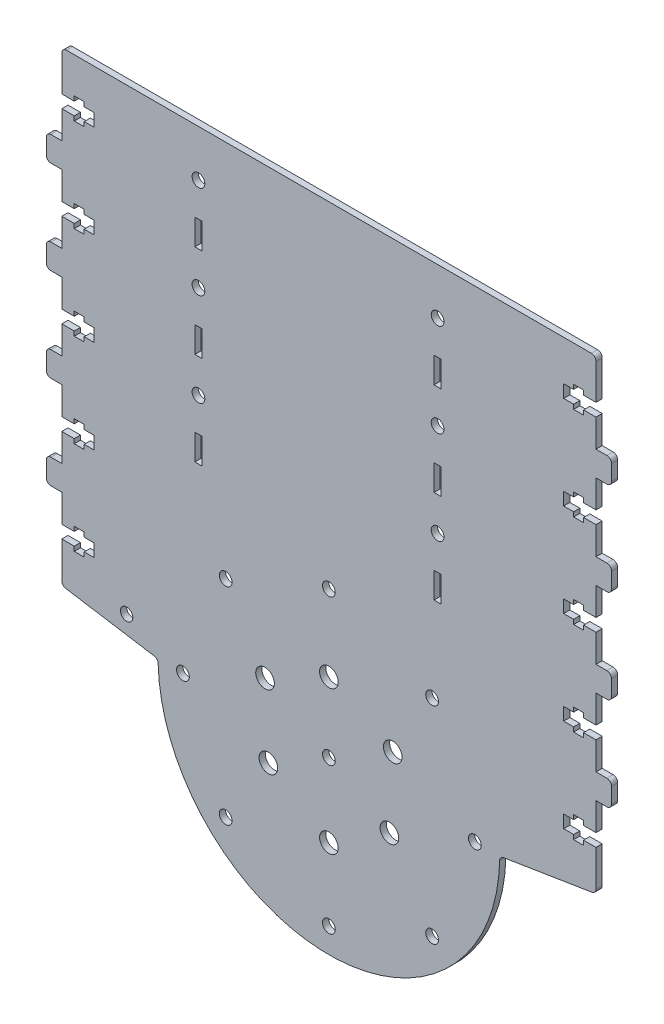
SolidWorks part; units mm, degrees
ref_plane "前视基准面" through (0, 0, 0) normal (0, 0, 1) x (1, 0, 0)
ref_plane "上视基准面" through (0, 0, 0) normal (0, 1, 0) x (1, 0, 0)
ref_plane "右视基准面" through (0, 0, 0) normal (1, 0, 0) x (0, 0, -1)
sketch "草图1" plane through (0, 0, 0) normal (0, 0, 1) x (1, 0, 0)
  line L9 (143, 45.95) -> (147, 45.95)
  line L10 (147, 45.95) -> (147, 44.5)
  line L11 (147, 44.5) -> (150.2, 44.5)
  line L12 (150.2, 44.5) -> (150.2, 45.95)
  line L13 (150.2, 45.95) -> (153.4, 45.95)
  line L14 (153.4, 45.95) -> (153.4, 50.05)
  line L23 (143, 48) -> (141.6922, 48) construction
  line L24 (143, 45.95) -> (143, 50.05) construction
  line L25 (150.2, 51.5) -> (150.2, 50.05)
  line L26 (147, 50.05) -> (147, 51.5)
  line L27 (150.2, 50.05) -> (153.4, 50.05)
  line L28 (147, 51.5) -> (150.2, 51.5)
  line L29 (143, 50.05) -> (147, 50.05)
  line L31 (143, 29) -> (138, 29)
  line L32 (138, 29) -> (138, 37)
  line L33 (138, 37) -> (143, 37)
  line L34 (143, 37) -> (143, 45.95)
  line L35 (138, 33) -> (143, 33) construction
  line L43 (143, 119) -> (143, 123)
  line L44 (229, -79) -> (229, -87) construction
  line L45 (143, 20.05) -> (143, 15.95) construction
  line L69 (143, -97) -> (311, -97) construction
  line L70 (143, 18) -> (141.6922, 18) construction
  line L71 (143, 15.95) -> (147, 15.95)
  line L72 (147, 15.95) -> (147, 14.5)
  line L73 (147, 14.5) -> (150.2, 14.5)
  line L98 (150.2, 14.5) -> (150.2, 15.95)
  line L123 (150.2, 15.95) -> (153.4, 15.95)
  line L124 (150.2, 21.5) -> (150.2, 20.05)
  line L125 (147, 20.05) -> (147, 21.5)
  line L126 (150.2, 20.05) -> (153.4, 20.05)
  line L127 (147, 21.5) -> (150.2, 21.5)
  line L128 (143, 20.05) -> (147, 20.05)
  line L129 (143, 7) -> (143, 15.95)
  line L130 (143, 15.95) -> (147, 15.95)
  line L131 (147, 14.5) -> (150.2, 14.5)
  line L132 (143, 15.95) -> (147, 15.95)
  line L133 (147, 15.95) -> (147, 14.5)
  line L134 (147, 14.5) -> (150.2, 14.5)
  line L135 (150.2, 14.5) -> (150.2, 15.95)
  line L136 (150.2, 15.95) -> (153.4, 15.95)
  line L137 (150.2, 21.5) -> (150.2, 20.05)
  line L138 (147, 20.05) -> (147, 21.5)
  line L139 (150.2, 20.05) -> (153.4, 20.05)
  line L140 (147, 21.5) -> (150.2, 21.5)
  line L141 (143, 20.05) -> (147, 20.05)
  line L142 (150.2, 15.95) -> (153.4, 15.95)
  line L143 (147, 15.95) -> (147, 14.5)
  line L144 (150.2, 14.5) -> (150.2, 15.95)
  line L145 (150.2, 20.05) -> (153.4, 20.05)
  line L146 (150.2, 21.5) -> (150.2, 20.05)
  line L147 (147, 21.5) -> (150.2, 21.5)
  line L148 (147, 20.05) -> (147, 21.5)
  line L149 (143, 20.05) -> (147, 20.05)
  line L150 (143, 45.95) -> (147, 45.95)
  line L151 (147, 45.95) -> (147, 44.5)
  line L152 (147, 44.5) -> (150.2, 44.5)
  line L153 (150.2, 44.5) -> (150.2, 45.95)
  line L154 (150.2, 45.95) -> (153.4, 45.95)
  line L155 (150.2, 51.5) -> (150.2, 50.05)
  line L156 (147, 50.05) -> (147, 51.5)
  line L157 (150.2, 50.05) -> (153.4, 50.05)
  line L158 (143, 45.95) -> (147, 45.95)
  line L159 (147, 44.5) -> (150.2, 44.5)
  line L160 (150.2, 45.95) -> (153.4, 45.95)
  line L161 (147, 45.95) -> (147, 44.5)
  line L162 (150.2, 44.5) -> (150.2, 45.95)
  line L163 (150.2, 50.05) -> (153.4, 50.05)
  line L164 (150.2, 51.5) -> (150.2, 50.05)
  line L165 (147, 51.5) -> (150.2, 51.5)
  line L166 (147, 50.05) -> (147, 51.5)
  line L167 (143, 50.05) -> (147, 50.05)
  line L168 (147, 51.5) -> (150.2, 51.5)
  line L169 (143, 50.05) -> (147, 50.05)
  line L170 (143, 29) -> (143, 20.05)
  line L171 (143, 15.95) -> (147, 15.95)
  line L172 (147, 14.5) -> (150.2, 14.5)
  line L173 (150.2, 15.95) -> (153.4, 15.95)
  line L174 (147, 15.95) -> (147, 14.5)
  line L175 (150.2, 14.5) -> (150.2, 15.95)
  line L177 (153.4, 20.05) -> (153.4, 15.95)
  line L178 (150.2, 20.05) -> (153.4, 20.05)
  line L179 (150.2, 21.5) -> (150.2, 20.05)
  line L180 (147, 21.5) -> (150.2, 21.5)
  line L181 (147, 20.05) -> (147, 21.5)
  line L182 (143, 20.05) -> (147, 20.05)
  line L183 (138, 3) -> (143, 3) construction
  line L184 (138, -1) -> (143, -1)
  line L185 (138, 7) -> (138, -1)
  line L186 (143, 7) -> (138, 7)
  line L187 (138, 93) -> (143, 93) construction
  line L188 (143, 78) -> (141.6922, 78) construction
  line L189 (272.15, 28.85) -> (269.85, 37.15) construction
  line L190 (138, 63) -> (143, 63) construction
  line L191 (143, 89) -> (138, 89)
  line L192 (138, 89) -> (138, 97)
  line L193 (138, 97) -> (143, 97)
  line L194 (143, 75.95) -> (147, 75.95)
  line L195 (147, 75.95) -> (147, 74.5)
  line L196 (147, 74.5) -> (150.2, 74.5)
  line L197 (150.2, 74.5) -> (150.2, 75.95)
  line L198 (150.2, 75.95) -> (153.4, 75.95)
  line L199 (143, 59) -> (143, 50.05)
  line L200 (138, 59) -> (143, 59)
  line L201 (153.4, 75.95) -> (153.4, 80.05)
  line L202 (150.2, 81.5) -> (150.2, 80.05)
  line L203 (143, 45.95) -> (147, 45.95)
  line L204 (147, 44.5) -> (150.2, 44.5)
  line L205 (150.2, 45.95) -> (153.4, 45.95)
  line L206 (147, 45.95) -> (147, 44.5)
  line L207 (150.2, 44.5) -> (150.2, 45.95)
  line L208 (150.2, 50.05) -> (153.4, 50.05)
  line L209 (150.2, 51.5) -> (150.2, 50.05)
  line L210 (147, 51.5) -> (150.2, 51.5)
  line L211 (147, 50.05) -> (147, 51.5)
  line L212 (143, 50.05) -> (147, 50.05)
  line L213 (272.15, 37.15) -> (269.85, 28.85) construction
  line L214 (147, 80.05) -> (147, 81.5)
  line L215 (150.2, 80.05) -> (153.4, 80.05)
  line L216 (147, 81.5) -> (150.2, 81.5)
  line L217 (143, 80.05) -> (147, 80.05)
  line L218 (143, 67) -> (143, 75.95)
  line L219 (143, 75.95) -> (147, 75.95)
  line L220 (147, 75.95) -> (147, 74.5)
  line L221 (147, 74.5) -> (150.2, 74.5)
  line L222 (150.2, 74.5) -> (150.2, 75.95)
  line L223 (150.2, 75.95) -> (153.4, 75.95)
  line L224 (150.2, 81.5) -> (150.2, 80.05)
  line L225 (147, 80.05) -> (147, 81.5)
  line L227 (271, 48) -> (271, 33) construction
  line L228 (272.15, 58.85) -> (269.85, 67.15) construction
  line L229 (272.15, 67.15) -> (269.85, 58.85) construction
  line L230 (150.2, 80.05) -> (153.4, 80.05)
  line L231 (143, 75.95) -> (147, 75.95)
  line L232 (147, 74.5) -> (150.2, 74.5)
  line L233 (150.2, 75.95) -> (153.4, 75.95)
  line L234 (147, 75.95) -> (147, 74.5)
  line L235 (150.2, 74.5) -> (150.2, 75.95)
  line L253 (150.2, 80.05) -> (153.4, 80.05)
  line L254 (150.2, 81.5) -> (150.2, 80.05)
  line L255 (143, -27) -> (143, -97) construction
  line L256 (147, 81.5) -> (150.2, 81.5)
  line L257 (147, 80.05) -> (147, 81.5)
  line L258 (143, 80.05) -> (147, 80.05)
  line L259 (147, 81.5) -> (150.2, 81.5)
  line L260 (143, 80.05) -> (147, 80.05)
  line L261 (143, 89) -> (143, 80.05)
  line L262 (143, 75.95) -> (147, 75.95)
  line L263 (147, 74.5) -> (150.2, 74.5)
  line L264 (150.2, 75.95) -> (153.4, 75.95)
  line L265 (147, 75.95) -> (147, 74.5)
  line L267 (150.2, 74.5) -> (150.2, 75.95)
  line L269 (150.2, 80.05) -> (153.4, 80.05)
  line L270 (150.2, 81.5) -> (150.2, 80.05)
  line L272 (147, 81.5) -> (150.2, 81.5)
  line L273 (147, 80.05) -> (147, 81.5)
  line L274 (143, 80.05) -> (147, 80.05)
  line L275 (138, 59) -> (143, 59)
  line L277 (138, 67) -> (138, 59)
  line L278 (143, 67) -> (138, 67)
  line L279 (143, 110.05) -> (143, 105.95) construction
  line L280 (143, 108) -> (141.6922, 108) construction
  line L281 (272.15, 88.85) -> (269.85, 97.15) construction
  line L282 (143, 105.95) -> (147, 105.95)
  line L283 (147, 105.95) -> (147, 104.5)
  line L284 (147, 104.5) -> (150.2, 104.5)
  line L285 (150.2, 104.5) -> (150.2, 105.95)
  line L286 (150.2, 105.95) -> (153.4, 105.95)
  line L287 (150.2, 111.5) -> (150.2, 110.05)
  line L288 (147, 110.05) -> (147, 111.5)
  line L289 (150.2, 110.05) -> (153.4, 110.05)
  line L290 (147, 111.5) -> (150.2, 111.5)
  line L291 (143, 110.05) -> (147, 110.05)
  line L292 (143, 97) -> (143, 105.95)
  line L293 (143, 105.95) -> (147, 105.95)
  line L294 (147, 104.5) -> (150.2, 104.5)
  line L296 (143, 105.95) -> (147, 105.95)
  line L300 (147, 105.95) -> (147, 104.5)
  line L301 (147, 104.5) -> (150.2, 104.5)
  line L302 (150.2, 104.5) -> (150.2, 105.95)
  line L303 (150.2, 105.95) -> (153.4, 105.95)
  line L304 (150.2, 111.5) -> (150.2, 110.05)
  line L305 (147, 110.05) -> (147, 111.5)
  line L306 (150.2, 110.05) -> (153.4, 110.05)
  line L307 (147, 111.5) -> (150.2, 111.5)
  line L308 (143, 110.05) -> (147, 110.05)
  line L309 (150.2, 105.95) -> (153.4, 105.95)
  line L310 (147, 105.95) -> (147, 104.5)
  line L312 (150.2, 104.5) -> (150.2, 105.95)
  line L314 (150.2, 110.05) -> (153.4, 110.05)
  line L315 (150.2, 111.5) -> (150.2, 110.05)
  line L317 (147, 111.5) -> (150.2, 111.5)
  line L320 (147, 110.05) -> (147, 111.5)
  line L321 (143, 110.05) -> (147, 110.05)
  line L322 (143, 119) -> (143, 110.05)
  line L323 (143, 105.95) -> (147, 105.95)
  line L324 (147, 104.5) -> (150.2, 104.5)
  line L325 (150.2, 105.95) -> (153.4, 105.95)
  line L326 (147, 105.95) -> (147, 104.5)
  line L327 (150.2, 104.5) -> (150.2, 105.95)
  line L328 (153.4, 110.05) -> (153.4, 105.95)
  line L329 (150.2, 110.05) -> (153.4, 110.05)
  line L330 (150.2, 111.5) -> (150.2, 110.05)
  line L331 (147, 111.5) -> (150.2, 111.5)
  line L332 (147, 110.05) -> (147, 111.5)
  line L333 (143, 110.05) -> (147, 110.05)
  line L334 (143, -14.05) -> (147, -14.05)
  line L335 (272.15, 97.15) -> (269.85, 88.85) construction
  line L336 (271, 108) -> (271, 48) construction
  line L337 (269.85, 37.15) -> (269.85, 28.85) construction
  line L338 (272.15, 28.85) -> (269.85, 28.85) construction
  line L339 (272.15, 37.15) -> (272.15, 28.85) construction
  line L340 (272.15, 37.15) -> (269.85, 37.15) construction
  line L341 (269.85, 67.15) -> (269.85, 58.85) construction
  line L342 (272.15, 58.85) -> (269.85, 58.85) construction
  line L343 (272.15, 67.15) -> (272.15, 58.85) construction
  line L344 (272.15, 67.15) -> (269.85, 67.15) construction
  line L345 (269.85, 97.15) -> (269.85, 88.85) construction
  line L346 (272.15, 88.85) -> (269.85, 88.85) construction
  line L347 (272.15, 97.15) -> (272.15, 88.85) construction
  line L348 (272.15, 97.15) -> (269.85, 97.15) construction
  line L349 (307.8, 110.05) -> (304.6, 110.05)
  line L350 (304.6, 110.05) -> (304.6, 105.95)
  line L352 (307.8, 105.95) -> (304.6, 105.95)
  line L353 (307.8, 110.05) -> (304.6, 110.05)
  line L355 (307.8, 105.95) -> (304.6, 105.95)
  line L357 (307.8, 110.05) -> (304.6, 110.05)
  line L358 (307.8, 105.95) -> (304.6, 105.95)
  line L359 (307.8, 110.05) -> (304.6, 110.05)
  line L360 (307.8, 105.95) -> (304.6, 105.95)
  line L361 (307.8, 80.05) -> (304.6, 80.05)
  line L362 (307.8, 75.95) -> (304.6, 75.95)
  line L363 (307.8, 80.05) -> (304.6, 80.05)
  line L364 (307.8, 75.95) -> (304.6, 75.95)
  line L365 (307.8, 80.05) -> (304.6, 80.05)
  line L367 (307.8, 75.95) -> (304.6, 75.95)
  line L369 (187, 108) -> (187, 48) construction
  line L370 (185.85, 97.15) -> (188.15, 97.15)
  line L371 (185.85, 97.15) -> (185.85, 88.85)
  line L372 (185.85, 88.85) -> (188.15, 88.85)
  line L373 (188.15, 97.15) -> (188.15, 88.85)
  line L374 (185.85, 97.15) -> (188.15, 88.85) construction
  line L375 (185.85, 88.85) -> (188.15, 97.15) construction
  line L387 (307.8, 80.05) -> (304.6, 80.05)
  line L389 (307.8, 50.05) -> (304.6, 50.05)
  line L391 (307.8, 45.95) -> (304.6, 45.95)
  line L392 (304.6, 75.95) -> (304.6, 80.05)
  line L420 (307.8, 75.95) -> (304.6, 75.95)
  line L421 (229, -32) -> (245.7973, -32) construction
  line L422 (229, -32) -> (253.7224, -46.2735) construction
  line L423 (185.85, 67.15) -> (188.15, 67.15)
  line L424 (185.85, 67.15) -> (185.85, 58.85)
  line L425 (185.85, 58.85) -> (188.15, 58.85)
  line L426 (188.15, 67.15) -> (188.15, 58.85)
  line L427 (185.85, 67.15) -> (188.15, 58.85) construction
  line L432 (185.85, 58.85) -> (188.15, 67.15) construction
  line L433 (307.8, 20.05) -> (304.6, 20.05)
  line L443 (187, 48) -> (187, 33) construction
  line L444 (304.6, 20.05) -> (304.6, 15.95)
  line L445 (185.85, 37.15) -> (188.15, 37.15)
  line L446 (185.85, 37.15) -> (185.85, 28.85)
  line L447 (185.85, 28.85) -> (188.15, 28.85)
  line L448 (188.15, 37.15) -> (188.15, 28.85)
  line L449 (185.85, 37.15) -> (188.15, 28.85) construction
  line L450 (185.85, 28.85) -> (188.15, 37.15) construction
  line L451 (307.8, 15.95) -> (304.6, 15.95)
  line L452 (307.8, 50.05) -> (304.6, 50.05)
  line L453 (307.8, 45.95) -> (304.6, 45.95)
  line L454 (307.8, 50.05) -> (304.6, 50.05)
  line L455 (307.8, 45.95) -> (304.6, 45.95)
  line L456 (307.8, 20.05) -> (304.6, 20.05)
  line L457 (307.8, 15.95) -> (304.6, 15.95)
  line L458 (307.8, 20.05) -> (304.6, 20.05)
  line L459 (307.8, 15.95) -> (304.6, 15.95)
  line L460 (307.8, 20.05) -> (304.6, 20.05)
  line L461 (307.8, 15.95) -> (304.6, 15.95)
  line L462 (307.8, 50.05) -> (304.6, 50.05)
  line L463 (304.6, 45.95) -> (304.6, 50.05)
  line L464 (307.8, 45.95) -> (304.6, 45.95)
  line L465 (315, 108) -> (316.3078, 108) construction
  line L466 (315, 110.05) -> (315, 105.95) construction
  line L467 (320, 63) -> (315, 63) construction
  line L468 (315, 78) -> (316.3078, 78) construction
  line L469 (320, 93) -> (315, 93) construction
  line L470 (320, 3) -> (315, 3) construction
  line L471 (315, 18) -> (316.3078, 18) construction
  line L472 (315, 20.05) -> (315, 15.95) construction
  line L473 (320, 33) -> (315, 33) construction
  line L474 (315, 45.95) -> (315, 50.05) construction
  line L475 (315, 48) -> (316.3078, 48) construction
  line L476 (315, -14.05) -> (315, -27)
  line L477 (315, 110.05) -> (311, 110.05)
  line L478 (311, 110.05) -> (311, 111.5)
  line L479 (311, 111.5) -> (307.8, 111.5)
  line L480 (307.8, 111.5) -> (307.8, 110.05)
  line L481 (307.8, 104.5) -> (307.8, 105.95)
  line L482 (311, 105.95) -> (311, 104.5)
  line L483 (311, 104.5) -> (307.8, 104.5)
  line L484 (315, 105.95) -> (311, 105.95)
  line L485 (315, 119) -> (315, 110.05)
  line L486 (315, 110.05) -> (311, 110.05)
  line L487 (311, 110.05) -> (311, 111.5)
  line L488 (311, 111.5) -> (307.8, 111.5)
  line L489 (307.8, 111.5) -> (307.8, 110.05)
  line L490 (307.8, 104.5) -> (307.8, 105.95)
  line L491 (311, 105.95) -> (311, 104.5)
  line L492 (315, 110.05) -> (311, 110.05)
  line L493 (311, 111.5) -> (307.8, 111.5)
  line L494 (311, 110.05) -> (311, 111.5)
  line L495 (307.8, 111.5) -> (307.8, 110.05)
  line L496 (307.8, 104.5) -> (307.8, 105.95)
  line L497 (311, 104.5) -> (307.8, 104.5)
  line L498 (311, 105.95) -> (311, 104.5)
  line L499 (315, 105.95) -> (311, 105.95)
  line L500 (311, 104.5) -> (307.8, 104.5)
  line L501 (315, 105.95) -> (311, 105.95)
  line L502 (315, 97) -> (315, 105.95)
  line L503 (315, 110.05) -> (311, 110.05)
  line L504 (311, 111.5) -> (307.8, 111.5)
  line L505 (311, 110.05) -> (311, 111.5)
  line L506 (307.8, 111.5) -> (307.8, 110.05)
  line L507 (307.8, 104.5) -> (307.8, 105.95)
  line L508 (311, 104.5) -> (307.8, 104.5)
  line L509 (311, 105.95) -> (311, 104.5)
  line L510 (315, 105.95) -> (311, 105.95)
  line L511 (315, 67) -> (320, 67)
  line L512 (320, 67) -> (320, 59)
  line L513 (320, 59) -> (315, 59)
  line L514 (315, 80.05) -> (311, 80.05)
  line L515 (311, 80.05) -> (311, 81.5)
  line L516 (311, 81.5) -> (307.8, 81.5)
  line L517 (307.8, 81.5) -> (307.8, 80.05)
  line L518 (307.8, 74.5) -> (307.8, 75.95)
  line L519 (311, 75.95) -> (311, 74.5)
  line L520 (311, 74.5) -> (307.8, 74.5)
  line L521 (315, 75.95) -> (311, 75.95)
  line L522 (315, 89) -> (315, 80.05)
  line L523 (315, 80.05) -> (311, 80.05)
  line L524 (311, 81.5) -> (307.8, 81.5)
  line L525 (315, 80.05) -> (311, 80.05)
  line L526 (311, 80.05) -> (311, 81.5)
  line L527 (311, 81.5) -> (307.8, 81.5)
  line L528 (307.8, 81.5) -> (307.8, 80.05)
  line L529 (307.8, 74.5) -> (307.8, 75.95)
  line L530 (311, 75.95) -> (311, 74.5)
  line L531 (311, 74.5) -> (307.8, 74.5)
  line L532 (315, 75.95) -> (311, 75.95)
  line L533 (311, 80.05) -> (311, 81.5)
  line L534 (307.8, 81.5) -> (307.8, 80.05)
  line L535 (307.8, 74.5) -> (307.8, 75.95)
  line L536 (311, 74.5) -> (307.8, 74.5)
  line L537 (311, 75.95) -> (311, 74.5)
  line L538 (315, 75.95) -> (311, 75.95)
  line L539 (315, 67) -> (315, 75.95)
  line L540 (315, 80.05) -> (311, 80.05)
  line L541 (311, 81.5) -> (307.8, 81.5)
  line L542 (311, 80.05) -> (311, 81.5)
  line L543 (315, 50.05) -> (311, 50.05)
  line L544 (311, 50.05) -> (311, 51.5)
  line L545 (311, 51.5) -> (307.8, 51.5)
  line L546 (307.8, 51.5) -> (307.8, 50.05)
  line L547 (307.8, 44.5) -> (307.8, 45.95)
  line L548 (311, 45.95) -> (311, 44.5)
  line L549 (311, 44.5) -> (307.8, 44.5)
  line L550 (315, 45.95) -> (311, 45.95)
  line L551 (307.8, 81.5) -> (307.8, 80.05)
  line L552 (320, 59) -> (315, 59)
  line L553 (315, 59) -> (315, 50.05)
  line L554 (307.8, 74.5) -> (307.8, 75.95)
  line L555 (311, 74.5) -> (307.8, 74.5)
  line L556 (311, 75.95) -> (311, 74.5)
  line L557 (315, 75.95) -> (311, 75.95)
  line L558 (320, 97) -> (315, 97)
  line L559 (320, 89) -> (320, 97)
  line L560 (315, 89) -> (320, 89)
  line L561 (315, 7) -> (320, 7)
  line L562 (320, 7) -> (320, -1)
  line L563 (320, -1) -> (315, -1)
  line L564 (315, 20.05) -> (311, 20.05)
  line L565 (311, 20.05) -> (311, 21.5)
  line L566 (311, 21.5) -> (307.8, 21.5)
  line L567 (307.8, 21.5) -> (307.8, 20.05)
  line L568 (307.8, 14.5) -> (307.8, 15.95)
  line L569 (311, 15.95) -> (311, 14.5)
  line L570 (311, 14.5) -> (307.8, 14.5)
  line L571 (315, 15.95) -> (311, 15.95)
  line L572 (315, 29) -> (315, 20.05)
  line L573 (315, 50.05) -> (311, 50.05)
  line L574 (311, 51.5) -> (307.8, 51.5)
  line L575 (315, 50.05) -> (311, 50.05)
  line L576 (311, 50.05) -> (311, 51.5)
  line L577 (311, 51.5) -> (307.8, 51.5)
  line L578 (307.8, 51.5) -> (307.8, 50.05)
  line L579 (307.8, 44.5) -> (307.8, 45.95)
  line L580 (311, 45.95) -> (311, 44.5)
  line L581 (311, 44.5) -> (307.8, 44.5)
  line L582 (315, 45.95) -> (311, 45.95)
  line L583 (311, 50.05) -> (311, 51.5)
  line L584 (307.8, 51.5) -> (307.8, 50.05)
  line L585 (307.8, 44.5) -> (307.8, 45.95)
  line L586 (311, 44.5) -> (307.8, 44.5)
  line L587 (311, 45.95) -> (311, 44.5)
  line L588 (315, 45.95) -> (311, 45.95)
  line L589 (315, 20.05) -> (311, 20.05)
  line L590 (311, 20.05) -> (311, 21.5)
  line L591 (311, 21.5) -> (307.8, 21.5)
  line L592 (307.8, 21.5) -> (307.8, 20.05)
  line L593 (307.8, 14.5) -> (307.8, 15.95)
  line L594 (311, 15.95) -> (311, 14.5)
  line L595 (315, 20.05) -> (311, 20.05)
  line L596 (311, 21.5) -> (307.8, 21.5)
  line L597 (311, 20.05) -> (311, 21.5)
  line L598 (307.8, 21.5) -> (307.8, 20.05)
  line L599 (307.8, 14.5) -> (307.8, 15.95)
  line L600 (311, 14.5) -> (307.8, 14.5)
  line L601 (311, 15.95) -> (311, 14.5)
  line L602 (315, 15.95) -> (311, 15.95)
  line L603 (311, 14.5) -> (307.8, 14.5)
  line L604 (315, 15.95) -> (311, 15.95)
  line L605 (315, 7) -> (315, 15.95)
  line L606 (315, 20.05) -> (311, 20.05)
  line L607 (311, 21.5) -> (307.8, 21.5)
  line L608 (311, 20.05) -> (311, 21.5)
  line L609 (307.8, 21.5) -> (307.8, 20.05)
  line L610 (307.8, 14.5) -> (307.8, 15.95)
  line L611 (311, 14.5) -> (307.8, 14.5)
  line L612 (311, 15.95) -> (311, 14.5)
  line L613 (315, 15.95) -> (311, 15.95)
  line L614 (315, 119) -> (315, 123)
  line L615 (315, 37) -> (315, 45.95)
  line L616 (320, 37) -> (315, 37)
  line L617 (320, 29) -> (320, 37)
  line L618 (315, 29) -> (320, 29)
  line L619 (315, 50.05) -> (311, 50.05)
  line L620 (311, 51.5) -> (307.8, 51.5)
  line L621 (311, 50.05) -> (311, 51.5)
  line L622 (307.8, 51.5) -> (307.8, 50.05)
  line L623 (307.8, 44.5) -> (307.8, 45.95)
  line L624 (311, 44.5) -> (307.8, 44.5)
  line L625 (311, 45.95) -> (311, 44.5)
  line L626 (315, 45.95) -> (311, 45.95)
  line L627 (315, 123) -> (143, 123)
  line L628 (143, -27) -> (174, -32)
  line L629 (284, -32) -> (315, -27)
  line L630 (147, -14.05) -> (147, -15.5)
  line L631 (147, -15.5) -> (150.2, -15.5)
  line L632 (150.2, -15.5) -> (150.2, -14.05)
  line L633 (150.2, -14.05) -> (153.4, -14.05)
  line L634 (153.4, -14.05) -> (153.4, -9.95)
  line L635 (150.2, -8.5) -> (150.2, -9.95)
  line L636 (147, -9.95) -> (147, -8.5)
  line L637 (150.2, -9.95) -> (153.4, -9.95)
  line L638 (147, -8.5) -> (150.2, -8.5)
  line L639 (143, -9.95) -> (147, -9.95)
  line L640 (143, -14.05) -> (147, -14.05)
  line L641 (147, -14.05) -> (147, -15.5)
  line L642 (147, -15.5) -> (150.2, -15.5)
  line L643 (150.2, -15.5) -> (150.2, -14.05)
  line L644 (150.2, -14.05) -> (153.4, -14.05)
  line L645 (150.2, -8.5) -> (150.2, -9.95)
  line L646 (147, -9.95) -> (147, -8.5)
  line L647 (150.2, -9.95) -> (153.4, -9.95)
  line L648 (143, -14.05) -> (147, -14.05)
  line L649 (147, -15.5) -> (150.2, -15.5)
  line L650 (150.2, -14.05) -> (153.4, -14.05)
  line L651 (147, -14.05) -> (147, -15.5)
  line L652 (150.2, -15.5) -> (150.2, -14.05)
  line L653 (150.2, -9.95) -> (153.4, -9.95)
  line L654 (150.2, -8.5) -> (150.2, -9.95)
  line L655 (147, -8.5) -> (150.2, -8.5)
  line L656 (147, -9.95) -> (147, -8.5)
  line L657 (143, -9.95) -> (147, -9.95)
  line L658 (147, -8.5) -> (150.2, -8.5)
  line L659 (143, -9.95) -> (147, -9.95)
  line L660 (143, -14.05) -> (147, -14.05)
  line L661 (147, -15.5) -> (150.2, -15.5)
  line L662 (150.2, -14.05) -> (153.4, -14.05)
  line L663 (147, -14.05) -> (147, -15.5)
  line L664 (150.2, -15.5) -> (150.2, -14.05)
  line L665 (150.2, -9.95) -> (153.4, -9.95)
  line L666 (150.2, -8.5) -> (150.2, -9.95)
  line L667 (147, -8.5) -> (150.2, -8.5)
  line L668 (147, -9.95) -> (147, -8.5)
  line L669 (143, -9.95) -> (147, -9.95)
  line L670 (143, -9.95) -> (143, -1)
  line L671 (143, -14.05) -> (143, -27)
  line L672 (315, -9.95) -> (315, -1)
  line L673 (315, -9.95) -> (311, -9.95)
  line L674 (311, -9.95) -> (311, -8.5)
  line L675 (311, -8.5) -> (307.8, -8.5)
  line L676 (307.8, -8.5) -> (307.8, -9.95)
  line L677 (307.8, -9.95) -> (304.6, -9.95)
  line L678 (307.8, -15.5) -> (307.8, -14.05)
  line L679 (311, -14.05) -> (311, -15.5)
  line L680 (307.8, -14.05) -> (304.6, -14.05)
  line L681 (311, -15.5) -> (307.8, -15.5)
  line L682 (315, -14.05) -> (311, -14.05)
  line L683 (315, -9.95) -> (311, -9.95)
  line L684 (311, -8.5) -> (307.8, -8.5)
  line L685 (315, -9.95) -> (311, -9.95)
  line L686 (311, -9.95) -> (311, -8.5)
  line L687 (311, -8.5) -> (307.8, -8.5)
  line L688 (307.8, -8.5) -> (307.8, -9.95)
  line L689 (307.8, -9.95) -> (304.6, -9.95)
  line L690 (307.8, -15.5) -> (307.8, -14.05)
  line L691 (311, -14.05) -> (311, -15.5)
  line L692 (307.8, -14.05) -> (304.6, -14.05)
  line L693 (311, -15.5) -> (307.8, -15.5)
  line L694 (315, -14.05) -> (311, -14.05)
  line L695 (307.8, -9.95) -> (304.6, -9.95)
  line L696 (311, -9.95) -> (311, -8.5)
  line L697 (307.8, -8.5) -> (307.8, -9.95)
  line L698 (307.8, -14.05) -> (304.6, -14.05)
  line L699 (307.8, -15.5) -> (307.8, -14.05)
  line L700 (311, -15.5) -> (307.8, -15.5)
  line L701 (311, -14.05) -> (311, -15.5)
  line L702 (315, -14.05) -> (311, -14.05)
  line L703 (315, -9.95) -> (311, -9.95)
  line L704 (311, -8.5) -> (307.8, -8.5)
  line L705 (307.8, -9.95) -> (304.6, -9.95)
  line L706 (311, -9.95) -> (311, -8.5)
  line L707 (307.8, -8.5) -> (307.8, -9.95)
  line L708 (304.6, -14.05) -> (304.6, -9.95)
  line L709 (307.8, -14.05) -> (304.6, -14.05)
  line L710 (307.8, -15.5) -> (307.8, -14.05)
  line L711 (311, -15.5) -> (307.8, -15.5)
  line L712 (311, -14.05) -> (311, -15.5)
  line L713 (315, -14.05) -> (311, -14.05)
  line L714 (264, 108) -> (264, 48) construction
  line L715 (262.85, 97.15) -> (265.15, 97.15)
  line L716 (262.85, 97.15) -> (262.85, 88.85)
  line L717 (262.85, 88.85) -> (265.15, 88.85)
  line L718 (265.15, 97.15) -> (265.15, 88.85)
  line L719 (262.85, 97.15) -> (265.15, 88.85) construction
  line L720 (262.85, 88.85) -> (265.15, 97.15) construction
  line L721 (262.85, 67.15) -> (265.15, 67.15)
  line L734 (271, 108) -> (264, 108) construction
  line L735 (262.85, 67.15) -> (262.85, 58.85)
  line L736 (262.85, 58.85) -> (265.15, 58.85)
  line L737 (265.15, 67.15) -> (265.15, 58.85)
  line L738 (262.85, 67.15) -> (265.15, 58.85) construction
  line L739 (262.85, 58.85) -> (265.15, 67.15) construction
  line L740 (264, 48) -> (264, 33) construction
  line L741 (262.85, 37.15) -> (265.15, 37.15)
  line L742 (262.85, 37.15) -> (262.85, 28.85)
  line L743 (262.85, 28.85) -> (265.15, 28.85)
  line L744 (265.15, 37.15) -> (265.15, 28.85)
  line L745 (262.85, 37.15) -> (265.15, 28.85) construction
  line L746 (262.85, 28.85) -> (265.15, 37.15) construction
  circle A88 centre (187, 108) radius 2.05
  circle A97 centre (229, -32) radius 23.75 construction
  circle A98 centre (229, -32) radius 22.5 construction
  circle A99 centre (229, -55.75) radius 3
  circle A100 centre (248.4856, -43.25) radius 3
  circle A101 centre (229, -32) radius 2.05
  circle A102 centre (276, -32) radius 2.05
  circle A103 centre (208.4319, -20.125) radius 3
  circle A104 centre (249.5681, -20.125) radius 3
  circle A105 centre (209.5144, -43.25) radius 3
  circle A106 centre (229, -9.5) radius 3
  circle A114 centre (187, 78) radius 2.05
  circle A115 centre (187, 48) radius 2.05
  circle A119 centre (262.234, -65.234) radius 2.05
  circle A120 centre (229, -79) radius 2.05
  circle A121 centre (195.766, -65.234) radius 2.05
  circle A122 centre (182, -32) radius 2.05
  circle A123 centre (195.766, 1.234) radius 2.05
  circle A124 centre (229, 15) radius 2.05
  circle A125 centre (262.234, 1.234) radius 2.05
  circle A126 centre (229, -32) radius 55 construction
  arc A127 (174, -32) -> (284, -32) centre (229, -32) ccw
  circle A128 centre (271, 48) radius 2.05 construction
  circle A129 centre (271, 78) radius 2.05 construction
  circle A130 centre (271, 108) radius 2.05 construction
  circle A131 centre (163.8583, -24.5718) radius 2
  circle A132 centre (264, 108) radius 2.05
  circle A133 centre (264, 78) radius 2.05
  circle A134 centre (264, 48) radius 2.05
  point P15 (142.3461, 48)
  point P103 (271, 63)
  point P104 (271, 93)
  point P199 (187, 93)
  point P208 (187, 63)
  point P238 (264, 93)
  point P284 (264, 63)
  dimension "D7" = 8
  dimension "D9" = 4.1
  dimension "D10" = 2.3
  dimension "D11" = 2.3
  dimension "D13" = 15
  dimension "D14" = 8.3
  dimension "D15" = 47.5
  dimension "D16" = 45
  dimension "D17" = 6
  dimension "D19" = 6
  dimension "D21" = 4.1
  dimension "D22" = 4.1
  dimension "D25" = 30
  dimension "D26" = 15
  dimension "D27" = 4.1
  dimension "D3" = 4
  dimension "D4" = 172
  dimension "D5" = 3.2
  dimension "D6" = 7
  dimension "D8" = 2.05
  dimension "D12" = 8.3
  dimension "D18" = 30
  dimension "D20" = 47
  dimension "D23" = 15
  dimension "D28" = 15
  dimension "D24" = 8
extrude "凸台-拉伸1" add sketch "草图1" along normal blind 2
sketch "草图2" plane through (143, 0, 0) normal (-1, 0, 0) x (0, 0, 1)
  line L0 (1, 20.05) -> (1, 15.95)
  line L1 (2, 20.05) -> (0, 20.05) construction
  line L2 (2, 15.95) -> (0, 15.95) construction
  circle A0 centre (1, 18) radius 2.05
sketch "草图3" plane through (315, 0, 0) normal (1, 0, 0) x (0, 0, -1)
  line L0 (-1, 15.95) -> (-1, 20.05)
  line L1 (-2, 15.95) -> (0, 15.95) construction
  line L2 (-2, 20.05) -> (0, 20.05) construction
  circle A0 centre (-1, 18) radius 2.05
fillet "圆角1" radius 1.5 22 edges at (284, -32, 1) (174, -32, 1) (315, 123, 1) (143, 123, 1) (138, 97, 1) (138, 67, 1) (138, 37, 1) (138, 29, 1) (138, 59, 1) (138, 89, 1) (138, 7, 1) (138, -1, 1) (143, -27, 1) (315, -27, 1) (320, 89, 1) (320, 97, 1) (320, 67, 1) (320, 59, 1) (320, 37, 1) (320, 29, 1) (320, 7, 1) (320, -1, 1)
